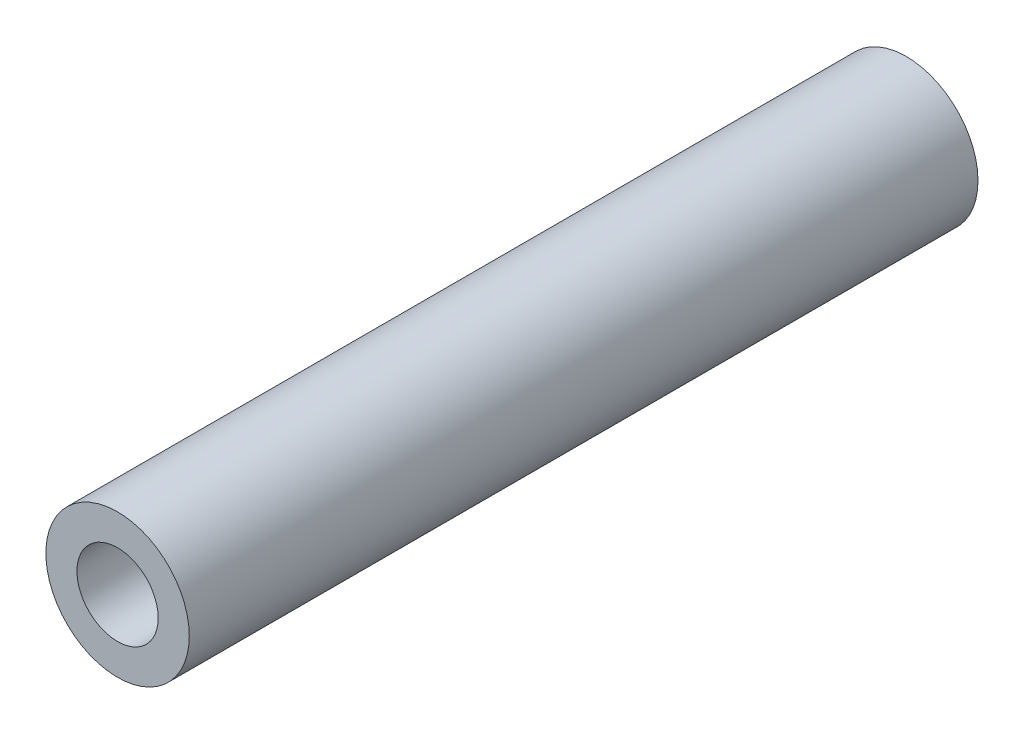
SolidWorks part; units mm, degrees
ref_plane "Front Plane" through (0, 0, 0) normal (0, 0, 1) x (1, 0, 0)
ref_plane "Top Plane" through (0, 0, 0) normal (0, 1, 0) x (1, 0, 0)
ref_plane "Right Plane" through (0, 0, 0) normal (1, 0, 0) x (0, 0, -1)
sketch "Sketch1" plane through (0, 0, 0) normal (0, 0, 1) x (1, 0, 0)
  circle A0 centre (0, 0) radius 3
  circle A1 centre (0, 0) radius 1.7
extrude "Ring_Envelope" add sketch "Sketch1" along normal blind 33
